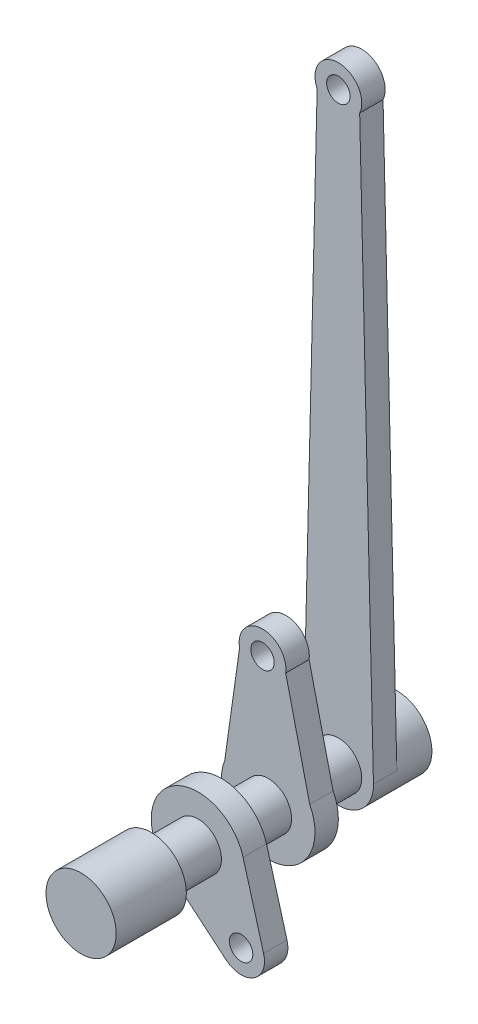
SolidWorks part; units mm, degrees
material "Aço cromo inoxidável"
ref_plane "Plano frontal" through (0, 0, 0) normal (0, 0, 1) x (1, 0, 0)
ref_plane "Plano superior" through (0, 0, 0) normal (0, 1, 0) x (1, 0, 0)
ref_plane "Plano direito" through (0, 0, 0) normal (1, 0, 0) x (0, 0, -1)
sketch "Esboço1" plane through (0, 0, 0) normal (0, 0, 1) x (1, 0, 0)
  circle A1 centre (0, 0) radius 15
extrude "Ressalto-extrusão1" add sketch "Esboço1" along normal blind 15
sketch "Esboço2" plane through (0, 0, 15) normal (0, 0, 1) x (1, 0, 0)
  line L2 (-9.0786, 245.8073) -> (-14.9956, 0.3615)
  line L3 (9.105, 245.865) -> (14.9957, 0.3598)
  arc A5 (9.105, 245.865) -> (-9.0786, 245.8073) centre (0, 250) ccw
  circle A6 centre (0, 0) radius 15 construction
  arc A7 (-14.9956, 0.3615) -> (14.9957, 0.3598) centre (0, 0) ccw
  point P1 (5.4588, 116.6214)
  point P3 (-8.7833, 120.2195)
  point P10 (9.105, 120.8073)
  dimension "D2" = 250
  dimension "D1" = 20
extrude "Ressalto-extrusão2" add sketch "Esboço2" along normal blind 10
sketch "Esboço4" plane through (0, 0, 25) normal (0, 0, 1) x (1, 0, 0)
  circle A1 centre (0, 0) radius 10
extrude "Ressalto-extrusão3" add sketch "Esboço4" along normal blind 20
sketch "Esboço9" plane through (0, 0, 25) normal (0, 0, 1) x (1, 0, 0)
  circle A0 centre (0, 250) radius 5
extrude "Corte-extrusão3" cut sketch "Esboço9" against normal through all both and the other way through all
sketch "Esboço11" plane through (0, 0, 45) normal (0, 0, 1) x (0.999, 0.0447, 0)
  line L0 (0, 0) -> (0, 142.342) construction
  line L2 (-9.8905, 52.7043) -> (-18.2329, 8.2196)
  line L3 (9.8302, 52.3451) -> (18.1437, 8.4147)
  arc A2 (9.8302, 52.3451) -> (-9.8905, 52.7043) centre (0, 54.18) ccw
  arc A3 (-18.2329, 8.2196) -> (18.1437, 8.4147) centre (0, 0) ccw
  dimension "D2" = 54.18
  dimension "D3" = 20
  dimension "D1" = 10
extrude "Ressalto-extrusão6" add sketch "Esboço11" along normal blind 10
sketch "Esboço12" plane through (0, 0, 55) normal (0, 0, 1) x (1, 0, 0)
  line L0 (-2.6847, 64.1224) -> (-2.42, 54.1259) construction
  arc A0 (7.4824, 52.732) -> (-12.2347, 52.2099) centre (-2.42, 54.1259) ccw construction
  circle A1 centre (-2.42, 54.1259) radius 5
extrude "Corte-extrusão4" cut sketch "Esboço12" against normal blind 10 and the other way through all
sketch "Esboço13" plane through (0, 0, 55) normal (0, 0, 1) x (1, 0, 0)
  circle A0 centre (0, 0) radius 10
extrude "Ressalto-extrusão7" add sketch "Esboço13" along normal blind 20
sketch "Esboço14" plane through (0, 0, 75) normal (0, 0, 1) x (-0.8402, -0.5423, 0)
  line L0 (-9.5566, 36.9046) -> (-19.1133, 5.8893)
  line L1 (9.5566, 36.9046) -> (19.1133, 5.8893)
  arc A0 (-19.1133, 5.8893) -> (19.1133, 5.8893) centre (0, 0) ccw
  arc A1 (9.5566, 36.9046) -> (-9.5566, 36.9046) centre (0, 33.96) ccw
  circle A2 centre (0, 33.96) radius 5
  dimension "D1" = 20
  dimension "D3" = 20
  dimension "D2" = 33.96
extrude "Ressalto-extrusão8" add sketch "Esboço14" along normal blind 10
sketch "Esboço15" plane through (0, 0, 85) normal (0, 0, 1) x (1, 0, 0)
  circle A0 centre (0, 0) radius 10
extrude "Ressalto-extrusão9" add sketch "Esboço15" along normal blind 20
sketch "Esboço17" plane through (0, 0, 105) normal (0, 0, 1) x (1, 0, 0)
  circle A0 centre (0, 0) radius 15
extrude "Ressalto-extrusão10" add sketch "Esboço17" along normal blind 30
